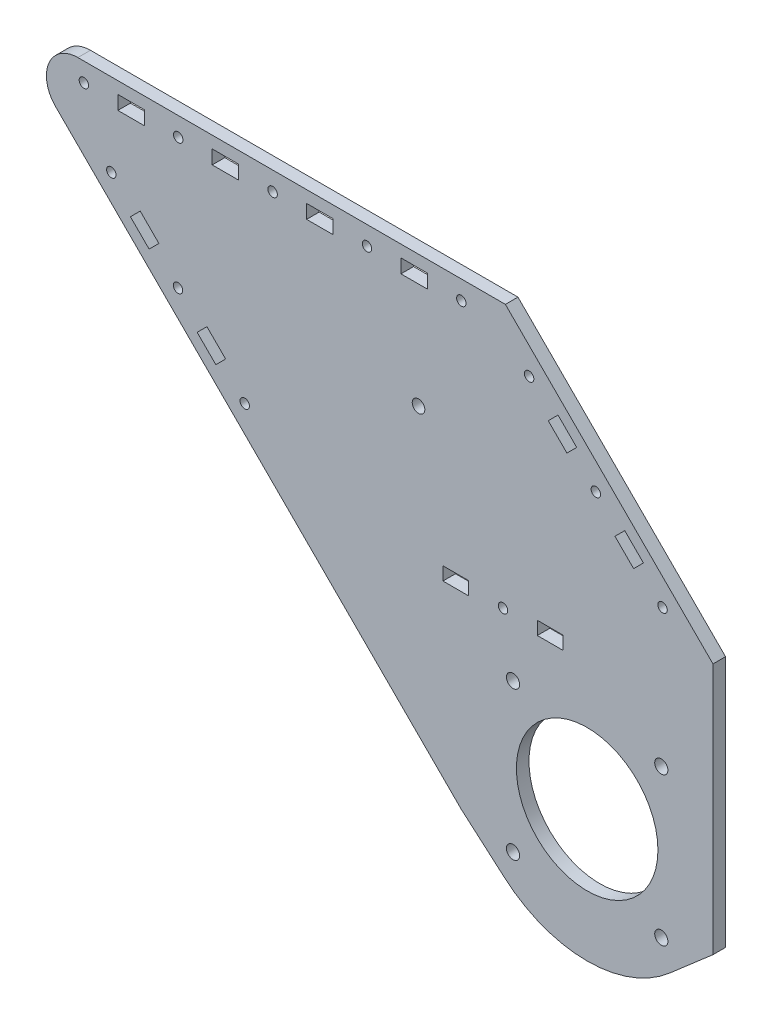
SolidWorks part; units mm, degrees
ref_plane "前视基准面" through (0, 0, 0) normal (0, 0, 1) x (1, 0, 0)
ref_plane "上视基准面" through (0, 0, 0) normal (0, 1, 0) x (1, 0, 0)
ref_plane "右视基准面" through (0, 0, 0) normal (1, 0, 0) x (0, 0, -1)
sketch "草图1" plane through (0, 0, 0) normal (0, 0, 1) x (1, 0, 0)
  line L261 (47.0274, 35.0547) -> (47.0274, 15.0547) construction
  line L315 (7.0274, -5.0025) -> (20.8108, -16.9604)
  line L316 (-52.9726, 135.0547) -> (-52.9726, 126.7057) construction
  line L332 (-112.9726, 135.0547) -> (-97.9726, 135.0547) construction
  line L334 (-42.1726, 137.2547) -> (-33.7726, 137.2547)
  line L335 (-42.1726, 137.2547) -> (-42.1726, 132.8547)
  line L336 (-42.1726, 132.8547) -> (-33.7726, 132.8547)
  line L337 (-33.7726, 137.2547) -> (-33.7726, 132.8547)
  line L338 (-42.1726, 137.2547) -> (-33.7726, 132.8547) construction
  line L339 (-42.1726, 132.8547) -> (-33.7726, 137.2547) construction
  line L389 (-114.8877, 141.0547) -> (21.0274, 141.0547)
  line L390 (-22.9726, 135.0547) -> (-22.9726, 144.5851) construction
  line L395 (-37.9726, 135.0547) -> (-7.9726, 135.0547) construction
  line L418 (87.0274, 75.0547) -> (21.0274, 141.0547)
  line L419 (-3.7726, 132.8547) -> (-12.1726, 137.2547) construction
  line L420 (-3.7726, 137.2547) -> (-12.1726, 132.8547) construction
  line L421 (7.0274, 135.0547) -> (-7.9726, 135.0547) construction
  line L422 (-12.1726, 137.2547) -> (-12.1726, 132.8547)
  line L423 (-3.7726, 132.8547) -> (-12.1726, 132.8547)
  line L424 (-3.7726, 137.2547) -> (-3.7726, 132.8547)
  line L443 (-3.7726, 137.2547) -> (-12.1726, 137.2547)
  line L444 (-102.1726, 137.2547) -> (-93.7726, 132.8547) construction
  line L445 (-102.1726, 132.8547) -> (-93.7726, 137.2547) construction
  line L446 (7.0274, -5.0025) -> (-139.0298, 141.0547) construction
  line L447 (-67.9726, 135.0547) -> (-97.9726, 135.0547) construction
  line L448 (47.0274, 15.0547) -> (7.0431, -54.2363) construction
  line L449 (-63.7726, 132.8547) -> (-72.1726, 137.2547) construction
  line L483 (-63.7726, 137.2547) -> (-72.1726, 132.8547) construction
  line L515 (47.0274, 35.0547) -> (47.0274, 135.0547) construction
  line L516 (47.0274, 135.0547) -> (-52.9726, 135.0547) construction
  line L517 (-102.1726, 137.2547) -> (-93.7726, 137.2547)
  line L518 (-102.1726, 137.2547) -> (-102.1726, 132.8547)
  line L519 (-102.1726, 132.8547) -> (-93.7726, 132.8547)
  line L520 (-93.7726, 137.2547) -> (-93.7726, 132.8547)
  line L521 (-72.1726, 137.2547) -> (-72.1726, 132.8547)
  line L522 (-63.7726, 132.8547) -> (-72.1726, 132.8547)
  line L523 (-63.7726, 137.2547) -> (-63.7726, 132.8547)
  line L524 (-63.7726, 137.2547) -> (-72.1726, 137.2547)
  line L525 (7.0274, -5.0025) -> (-7.4159, -49.5482) construction
  line L551 (7.0274, -5.0025) -> (87.0274, -5.0025) construction
  line L552 (7.0274, -5.0025) -> (7.0274, 75.0547) construction
  line L553 (7.0274, 75.0547) -> (87.0274, 75.0547) construction
  line L554 (87.0274, -5.0025) -> (87.0274, 75.0547)
  line L555 (87.0274, -5.0025) -> (17.0006, -65.7205) construction
  line L556 (21.4033, 132.1936) -> (81.3921, 72.2048) construction
  line L557 (54.0274, 108.0547) -> (35.0674, 89.0947) construction
  line L558 (43.7037, 113.0045) -> (34.6527, 115.8329) construction
  line L559 (55.8659, 94.6197) -> (61.8056, 88.68)
  line L576 (55.8659, 94.6197) -> (58.9772, 97.731)
  line L577 (58.9772, 97.731) -> (64.9169, 91.7913)
  line L578 (61.8056, 88.68) -> (64.9169, 91.7913)
  line L579 (55.8659, 94.6197) -> (64.9169, 91.7913) construction
  line L580 (58.9772, 97.731) -> (61.8056, 88.68) construction
  line L581 (40.5924, 109.8932) -> (37.764, 118.9442) construction
  line L582 (34.6527, 115.8329) -> (37.764, 118.9442)
  line L583 (43.7037, 113.0045) -> (37.764, 118.9442)
  line L584 (40.5924, 109.8932) -> (43.7037, 113.0045)
  line L585 (40.5924, 109.8932) -> (34.6527, 115.8329)
  line L586 (60.3914, 93.2055) -> (58.8358, 91.6499) construction
  line L587 (39.1782, 114.4187) -> (37.6226, 112.8631) construction
  line L589 (20.2758, 57.0547) -> (5.2758, 57.0547) construction
  line L594 (73.2276, -16.9678) -> (87.0274, -5.0025)
  line L599 (-90.2039, 92.2289) -> (-121.9587, 123.9837)
  line L600 (-73.8521, 87.4736) -> (-76.9634, 84.3624)
  line L605 (-25.9726, 27.9975) -> (-21.7299, 32.2402) construction
  line L607 (-83.0445, 93.5547) -> (-87.2872, 89.3121) construction
  line L608 (-90.2039, 92.2289) -> (7.0274, -5.0025)
  line L621 (-83.0445, 93.5547) -> (-61.8313, 72.3415) construction
  line L622 (-73.8521, 87.4736) -> (-67.9124, 81.5339)
  line L623 (47.0274, 15.0547) -> (89.2922, -52.8694) construction
  line L624 (89.2922, -52.8694) -> (7.0274, -54.2273) construction
  line L625 (-76.9634, 84.3624) -> (-71.0237, 78.4227)
  line L630 (-67.9124, 81.5339) -> (-71.0237, 78.4227)
  line L631 (-73.8521, 87.4736) -> (-71.0237, 78.4227) construction
  line L632 (-82.9726, 135.0547) -> (-82.9726, 64.2144) construction
  line L633 (-76.9634, 84.3624) -> (-67.9124, 81.5339) construction
  line L634 (-89.1256, 102.7471) -> (-92.2369, 99.6359)
  line L635 (-92.2369, 99.6359) -> (-98.1766, 105.5756)
  line L636 (-95.0653, 108.6868) -> (-98.1766, 105.5756)
  line L637 (-89.1256, 102.7471) -> (-95.0653, 108.6868)
  line L638 (-22.9726, 135.0547) -> (-22.9726, 124.9547) construction
  line L639 (-22.9726, 124.9547) -> (47.0274, 15.0547) construction
  line L640 (20.2758, 57.0547) -> (20.2758, 57.6954) construction
  line L641 (9.3758, 54.9547) -> (1.1758, 54.9547)
  line L642 (9.3758, 54.9547) -> (9.3758, 59.1547)
  line L643 (9.3758, 59.1547) -> (1.1758, 59.1547)
  line L644 (1.1758, 54.9547) -> (1.1758, 59.1547)
  line L645 (9.3758, 54.9547) -> (1.1758, 59.1547) construction
  line L646 (9.3758, 59.1547) -> (1.1758, 54.9547) construction
  line L647 (31.1758, 59.1547) -> (39.3758, 54.9547) construction
  line L648 (31.1758, 54.9547) -> (39.3758, 59.1547) construction
  line L649 (39.3758, 54.9547) -> (39.3758, 59.1547)
  line L650 (31.1758, 59.1547) -> (39.3758, 59.1547)
  line L651 (31.1758, 54.9547) -> (31.1758, 59.1547)
  line L652 (31.1758, 54.9547) -> (39.3758, 54.9547)
  circle A39 centre (-52.9726, 135.0547) radius 1.5
  circle A42 centre (47.0274, 15.0547) radius 22.5
  circle A49 centre (-22.9726, 135.0547) radius 1.5
  circle A69 centre (7.0274, 135.0547) radius 1.5
  circle A92 centre (-112.9726, 135.0547) radius 1.5
  circle A93 centre (-82.9726, 135.0547) radius 1.5
  circle A94 centre (7.0431, -54.2363) radius 5.2 construction
  circle A96 centre (7.0431, -54.2363) radius 15.2 construction
  circle A98 centre (49.7848, 103.8121) radius 1.5
  circle A99 centre (70.998, 82.5989) radius 1.5
  circle A100 centre (28.5716, 125.0253) radius 1.5
  circle A107 centre (70.5974, 38.6247) radius 2.1
  circle A108 centre (70.5974, -8.5153) radius 2.1
  circle A109 centre (23.4574, -8.5153) radius 2.1
  circle A110 centre (23.4574, 38.6247) radius 2.1
  arc A111 (73.2276, -16.9678) -> (20.8108, -16.9604) centre (47.0235, 13.2537) cw
  arc A115 (-114.8877, 141.0547) -> (-121.9587, 123.9837) centre (-114.8877, 131.0547) ccw
  circle A116 centre (-83.0445, 93.5547) radius 1.5
  circle A117 centre (-61.8313, 72.3415) radius 1.5
  circle A118 centre (-104.2577, 114.7679) radius 1.5
  circle A121 centre (20.2758, 57.0547) radius 1.5
  circle A122 centre (-6.5853, 99.2267) radius 2
  point P5 (210.9534, 218.4629)
  point P6 (288.6284, 218.4629)
  point P54 (-105.4726, 135.0547)
  point P60 (60.3914, 93.2055)
  point P88 (-72.4379, 82.9481)
  point P115 (47.016, -39.6951)
  dimension "D1" = 40
  dimension "D3" = 45
  dimension "D5" = 23.57
  dimension "D4" = 4.2
  dimension "D6" = 23.57
  dimension "D2" = 40
  dimension "D7" = 6
  dimension "D12" = 3
  dimension "D19" = 10.4
  dimension "D20" = 10
  dimension "D22" = 3
  dimension "D8" = 30
  dimension "D28" = 40
  dimension "D26" = 10
  dimension "D17" = 10.1
  dimension "D29" = 42
  dimension "D30" = 50
  dimension "D31" = 15
  dimension "D9" = 15
  dimension "D10" = 15
  dimension "D11" = 8.4
  dimension "D13" = 4.4
  dimension "D14" = 6
  dimension "D15" = 45
  dimension "D16" = 41.5
  dimension "D18" = 80
  dimension "D21" = 6
  dimension "D23" = 15
  dimension "D24" = 8.4
  dimension "D25" = 4.4
  dimension "D27" = 4
  dimension "D32" = 8.2
  dimension "D33" = 4.2
  dimension "D34" = 120
  dimension "D35" = 70
extrude "凸台-拉伸1" add sketch "草图1" along normal blind 4
sketch "草图2" plane through (0, 0, 4) normal (0, 0, 1) x (1, 0, 0)
  line L0 (47.0274, 15.0547) -> (-6.5853, 99.2267)
  line L1 (-6.5853, 99.2267) -> (-33.2273, 141.0547)
  line L2 (21.0274, 141.0547) -> (-114.8877, 141.0547) construction
  line L3 (-22.9726, 135.0547) -> (-22.9726, 124.9547)
  line L5 (39.3758, 54.9547) -> (31.1758, 54.9547)
  line L6 (39.3758, 54.9547) -> (39.3758, 59.1547)
  line L7 (39.3758, 59.1547) -> (31.1758, 59.1547)
  line L8 (31.1758, 54.9547) -> (31.1758, 59.1547)
  line L13 (-33.7726, 132.8547) -> (-42.1726, 132.8547)
  line L14 (-33.7726, 132.8547) -> (-33.7726, 137.2547)
  line L15 (-33.7726, 137.2547) -> (-42.1726, 137.2547)
  line L16 (-42.1726, 132.8547) -> (-42.1726, 137.2547)
  line L17 (9.3758, 54.9547) -> (1.1758, 54.9547)
  line L18 (9.3758, 54.9547) -> (9.3758, 59.1547)
  line L19 (9.3758, 59.1547) -> (1.1758, 59.1547)
  line L20 (1.1758, 54.9547) -> (1.1758, 59.1547)
  circle A1 centre (-22.9726, 135.0547) radius 1.5
  circle A2 centre (-6.5853, 99.2267) radius 2
  circle A3 centre (20.2758, 57.0547) radius 1.5
  circle A4 centre (47.0274, 15.0547) radius 22.5
